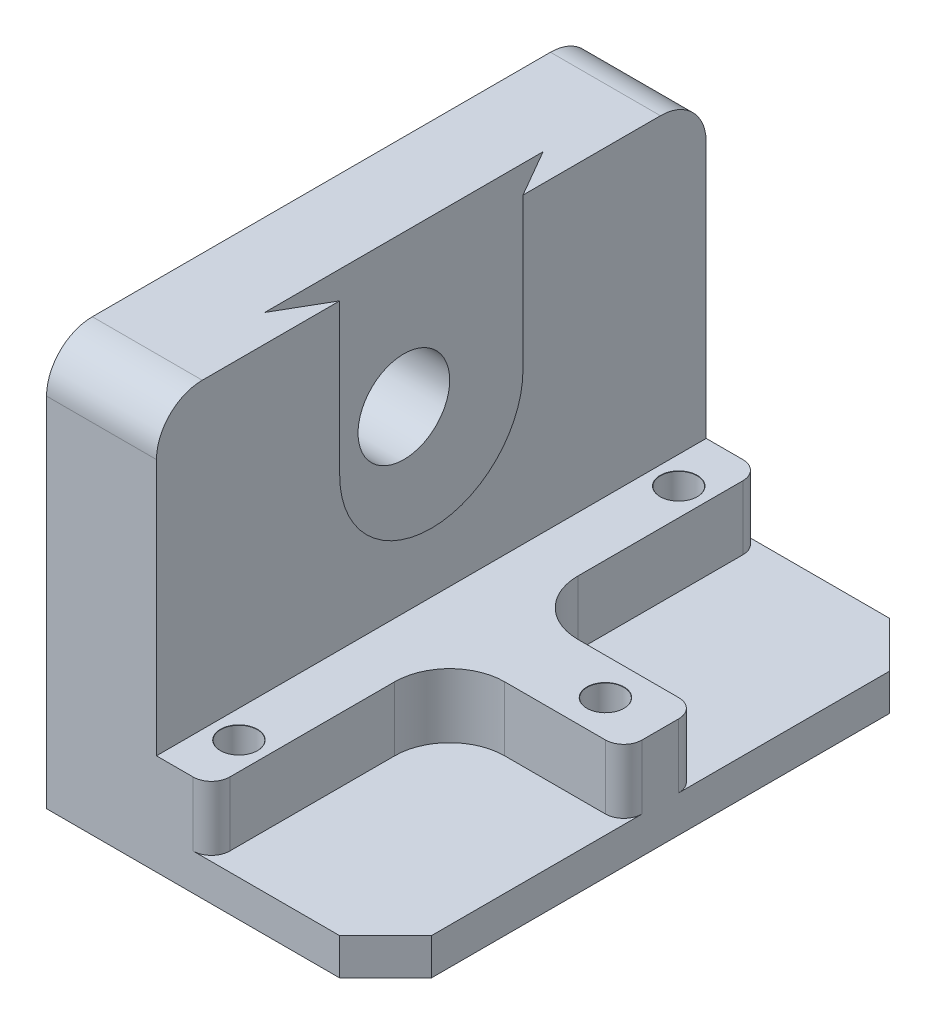
SolidWorks part; units mm, degrees
ref_plane "Piano frontale" through (0, 0, 0) normal (0, 0, 1) x (1, 0, 0)
ref_plane "Piano superiore" through (0, 0, 0) normal (0, 1, 0) x (1, 0, 0)
ref_plane "Piano destro" through (0, 0, 0) normal (1, 0, 0) x (0, 0, -1)
sketch "Schizzo1" plane through (0, 0, 0) normal (0, 0, 1) x (1, 0, 0)
  line L0 (0, 44) -> (0, 0)
  line L1 (0, 0) -> (37, 0)
  line L2 (37, 0) -> (37, 4)
  line L3 (37, 4) -> (12, 4)
  line L4 (12, 4) -> (12, 44)
  line L5 (12, 44) -> (0, 44)
  dimension "D1" = 44
  dimension "D2" = 40
  dimension "D3" = 37
  dimension "D4" = 25
extrude "Estrusione-Estrusione1" add sketch "Schizzo1" along normal mid plane 60
sketch "Schizzo2" plane through (12, 0, 0) normal (1, 0, 0) x (0, 0, -1)
  line L0 (0, 0) -> (0, 44) construction
  line L1 (-10, 42.376) -> (-10, 44)
  line L2 (10, 42.376) -> (10, 44)
  line L3 (-30, 44) -> (30, 44) construction
  line L6 (-30, 27.5) -> (30, 27.5) construction
  line L7 (-10, 44) -> (10, 44)
  line L8 (30, 4) -> (30, 44) construction
  line L9 (-30, 0) -> (30, 0) construction
  line L11 (0, 42.376) -> (0, 27.5) construction
  line L12 (10, 42.376) -> (10, 27.5)
  line L13 (-10, 42.376) -> (-10, 27.5)
  arc A3 (-10, 27.5) -> (10, 27.5) centre (0, 27.5) ccw
  point P4 (0, 34.938)
  point P9 (0, 27.5)
  dimension "D2" = 20
  dimension "D1" = 27.5
  dimension "D3" = 30
sketch "Schizzo3" plane through (0, 4, 0) normal (0, 1, 0) x (1, 0, 0)
  line L0 (0, 0) -> (37, 0) construction
  line L1 (0, -30) -> (0, 30) construction
  line L2 (37, -30) -> (37, 30) construction
  line L3 (12, 30) -> (18, 30)
  line L4 (37, 30) -> (12, 30) construction
  line L5 (18, 30) -> (18, 4)
  line L6 (18, 4) -> (37, 4)
  line L7 (37, 4) -> (37, -4)
  line L8 (12, -30) -> (18, -30)
  line L9 (18, -4) -> (37, -4)
  line L10 (18, -30) -> (18, -4)
  line L11 (12, 30) -> (12, -30)
  dimension "D1" = 26
  dimension "D3" = 19
extrude "Estrusione-Estrusione2" add sketch "Schizzo3" along normal blind 7
hole_wizard "Foro Ø10.0 (10)-1" positions "Schizzo3D1" profile "Schizzo6" hole size "Ø10.0" standard "ISO" end condition up to next
sketch3d "Schizzo3D1"
  point P0 (12, 27.5, 0)
sketch "Schizzo6" plane through (12, 27.5, 0) normal (0, 1, 0) x (0, 0, -1)
  line L0 (0, 0) -> (0, 12)
  line L1 (0, 12) -> (5, 12)
  line L2 (5, 12) -> (5, 0.025)
  line L3 (5, 0.025) -> (5.025, 0)
  line L5 (5.025, 0) -> (0, 0)
  line L6 (-5, 0.025) -> (-5.025, 0) construction
  line L11 (0, -6.35) -> (0, 107.95) construction
  dimension "Thru Hole Dia." = 10
  dimension "Thru Hole Depth" = 12
  dimension "Near C'Sink Dia." = 10.05
  dimension "Near C'Sink Angle" = 90
hole_wizard "Foro Ø4.0 (4)-1" positions "Schizzo3D2" profile "Schizzo7" hole size "Ø4.0" standard "ISO" end condition up to next
sketch3d "Schizzo3D2"
  line L3 (37, 11, 0) -> (12, 11, 0) construction
  line L4 (37, 11, 4) -> (37, 11, -4) construction
  line L5 (12, 11, -30) -> (12, 11, 30) construction
  line L6 (15, 11, 30) -> (15, 11, 0) construction
  line L7 (12, 11, 30) -> (18, 11, 30) construction
  line L9 (18, 11, 24) -> (12, 11, 24) construction
  line L10 (18, 11, 30) -> (18, 11, 4) construction
  line L11 (31, 11, 4) -> (31, 11, -44.483) construction
  line L12 (18, 11, 4) -> (37, 11, 4) construction
  line L13 (15, 11, 0) -> (15, 11, -30) construction
  line L14 (18, 11, -30) -> (12, 11, -30) construction
  line L16 (12, 11, -24) -> (18, 11, -24) construction
  line L17 (18, 11, -4) -> (18, 11, -30) construction
  point P28 (31, 11, 0)
  point P30 (15, 11, 24)
  point P33 (31, 11, 0)
  point P37 (15, 11, 24)
  point P51 (15, 11, -24)
  point P53 (15, 11, -24)
  dimension "D1" = 3
  dimension "D2" = 24
  dimension "D3" = 6
  dimension "D4" = 24
sketch "Schizzo7" plane through (15, 11, -24) normal (1, 0, 0) x (0, 0, 1)
  line L0 (0, 0) -> (0, 11.001)
  line L1 (0, 11.001) -> (2, 11.001)
  line L2 (2, 11.001) -> (2, 0.025)
  line L3 (2, 0.025) -> (2.025, 0)
  line L5 (2.025, 0) -> (0, 0)
  line L6 (-2, 0.025) -> (-2.025, 0) construction
  line L11 (0, -6.35) -> (0, 107.95) construction
  dimension "Thru Hole Dia." = 4
  dimension "Thru Hole Depth" = 11.001
  dimension "Near C'Sink Dia." = 4.05
  dimension "Near C'Sink Angle" = 90
chamfer "Smusso1" distance 5 angle 45 2 edges at (37, 2, -30) (37, 2, 30)
fillet "Raccordo1" radius 2 4 edges at (18, 7.5, -30) (18, 7.5, 30) (37, 7.5, -4) (37, 7.5, 4)
fillet "Raccordo2" radius 6 2 edges at (18, 7.5, -4) (18, 7.5, 4)
fillet "Raccordo3" radius 5 2 edges at (6, 44, -30) (6, 44, 30)
extrude "Taglio-Estrusione4" cut sketch "Schizzo2" against normal blind 3 draft 60 draft outward yes
